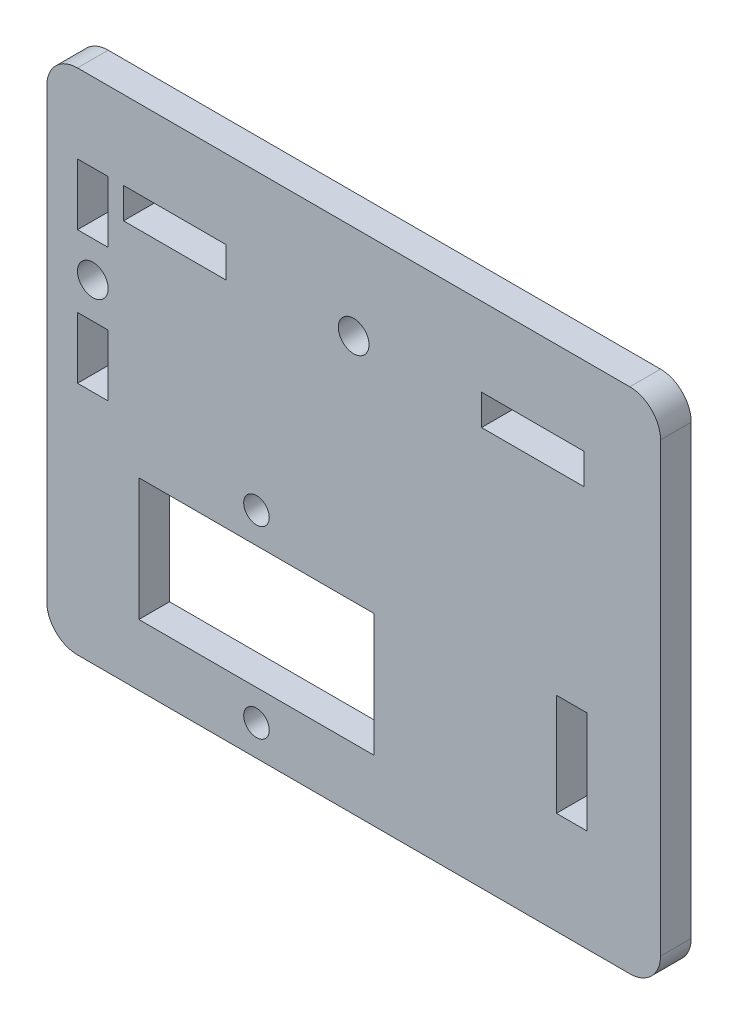
SolidWorks part; units mm, degrees
ref_plane "前基準面" through (0, 0, 0) normal (0, 0, 1) x (1, 0, 0)
ref_plane "上基準面" through (0, 0, 0) normal (0, 1, 0) x (1, 0, 0)
ref_plane "右基準面" through (0, 0, 0) normal (1, 0, 0) x (0, 0, -1)
sketch "草圖1" plane through (0, 0, 0) normal (0, 0, 1) x (1, 0, 0)
  line L0 (84.8241, 116) -> (84.8241, 106) construction
  line L1 (84.8241, 106) -> (81.8241, 106.0001) construction
  line L2 (81.8241, 116.0001) -> (84.8241, 116) construction
  line L3 (81.8241, 106.0001) -> (81.8241, 116.0001) construction
  line L4 (64.0003, 102.0001) -> (64.0004, 114.0001) construction
  line L5 (41.0003, 102.0003) -> (64.0003, 102.0001) construction
  line L6 (41.0004, 114.0003) -> (41.0003, 102.0003) construction
  line L7 (38.0004, 119.0003) -> (35.0004, 119.0003) construction
  line L8 (64.0004, 114.0001) -> (41.0004, 114.0003) construction
  line L9 (35.0004, 119.0003) -> (35.0004, 125.0003) construction
  line L10 (35.0004, 125.0003) -> (38.0004, 125.0003) construction
  line L11 (38.0004, 125.0003) -> (38.0004, 119.0003) construction
  line L12 (38.0005, 132.0003) -> (35.0005, 132.0003) construction
  line L13 (35.0005, 132.0003) -> (35.0005, 138.0003) construction
  line L14 (35.0005, 138.0003) -> (38.0005, 138.0003) construction
  line L15 (38.0005, 138.0003) -> (38.0005, 132.0003) construction
  line L16 (39.5005, 138.0003) -> (39.5005, 135.0003) construction
  line L17 (49.5005, 138.0002) -> (39.5005, 138.0003) construction
  line L18 (49.5005, 135.0002) -> (49.5005, 138.0002) construction
  line L19 (39.5005, 135.0003) -> (49.5005, 135.0002) construction
  line L20 (74.5005, 135.0001) -> (84.5005, 135) construction
  line L21 (74.5005, 138.0001) -> (74.5005, 135.0001) construction
  line L22 (84.5005, 138) -> (74.5005, 138.0001) construction
  line L23 (84.5005, 135) -> (84.5005, 138) construction
  line L24 (88.5005, 145.7) -> (35.0005, 145.7003) construction
  line L25 (84.8241, 116) -> (84.8241, 106)
  line L26 (84.8241, 106) -> (81.8241, 106.0001)
  line L27 (81.8241, 116.0001) -> (84.8241, 116)
  line L28 (81.8241, 106.0001) -> (81.8241, 116.0001)
  line L29 (64.0003, 102.0001) -> (64.0004, 114.0001)
  line L30 (41.0003, 102.0003) -> (64.0003, 102.0001)
  line L31 (41.0004, 114.0003) -> (41.0003, 102.0003)
  line L32 (38.0004, 119.0003) -> (35.0004, 119.0003)
  line L33 (64.0004, 114.0001) -> (41.0004, 114.0003)
  line L34 (35.0004, 119.0003) -> (35.0004, 125.0003)
  line L35 (35.0004, 125.0003) -> (38.0004, 125.0003)
  line L36 (38.0004, 125.0003) -> (38.0004, 119.0003)
  line L37 (38.0005, 132.0003) -> (35.0005, 132.0003)
  line L38 (35.0005, 132.0003) -> (35.0005, 138.0003)
  line L39 (35.0005, 138.0003) -> (38.0005, 138.0003)
  line L40 (38.0005, 138.0003) -> (38.0005, 132.0003)
  line L41 (39.5005, 138.0003) -> (39.5005, 135.0003)
  line L42 (49.5005, 138.0002) -> (39.5005, 138.0003)
  line L43 (49.5005, 135.0002) -> (49.5005, 138.0002)
  line L44 (39.5005, 135.0003) -> (49.5005, 135.0002)
  line L45 (74.5005, 135.0001) -> (84.5005, 135)
  line L46 (74.5005, 138.0001) -> (74.5005, 135.0001)
  line L47 (84.5005, 138) -> (74.5005, 138.0001)
  line L48 (84.5005, 135) -> (84.5005, 138)
  line L49 (88.5005, 145.7) -> (35.0005, 145.7003)
  line L50 (92.0004, 142.7) -> (92.0003, 99)
  line L51 (89.0003, 96) -> (35.0003, 96.0003)
  line L52 (32.0003, 99.0003) -> (32.0005, 142.7003)
  line L53 (89.0005, 145.7) -> (88.5005, 145.7)
  circle A0 centre (52.5004, 117.0002) radius 1.25 construction
  circle A1 centre (52.5003, 99.0002) radius 1.25 construction
  circle A2 centre (36.5005, 128.5003) radius 1.5 construction
  circle A3 centre (62.0005, 136.5002) radius 1.5 construction
  arc A4 (92.0004, 142.7) -> (89.0005, 145.7) centre (89.0004, 142.7) ccw construction
  arc A5 (89.0003, 96) -> (92.0003, 99) centre (89.0004, 98.9999) ccw construction
  arc A6 (32.0003, 99.0003) -> (35.0003, 96.0003) centre (34.9999, 98.9998) ccw construction
  arc A7 (35.0005, 145.7003) -> (32.0005, 142.7003) centre (35.0002, 142.7006) ccw construction
  circle A8 centre (52.5004, 117.0002) radius 1.25
  circle A9 centre (52.5003, 99.0002) radius 1.25
  circle A10 centre (36.5005, 128.5003) radius 1.5
  circle A11 centre (62.0005, 136.5002) radius 1.5
  arc A12 (92.0004, 142.7) -> (89.0005, 145.7) centre (89.0004, 142.7) ccw
  arc A13 (89.0003, 96) -> (92.0003, 99) centre (89.0004, 98.9999) ccw
  arc A14 (32.0003, 99.0003) -> (35.0003, 96.0003) centre (34.9999, 98.9998) ccw
  arc A15 (35.0005, 145.7003) -> (32.0005, 142.7003) centre (35.0002, 142.7006) ccw
  point P0 (74.5005, 135.0001)
  point P17 (88.5776, 145.7)
extrude "填料-伸長1" add sketch "草圖1" along normal blind 3
